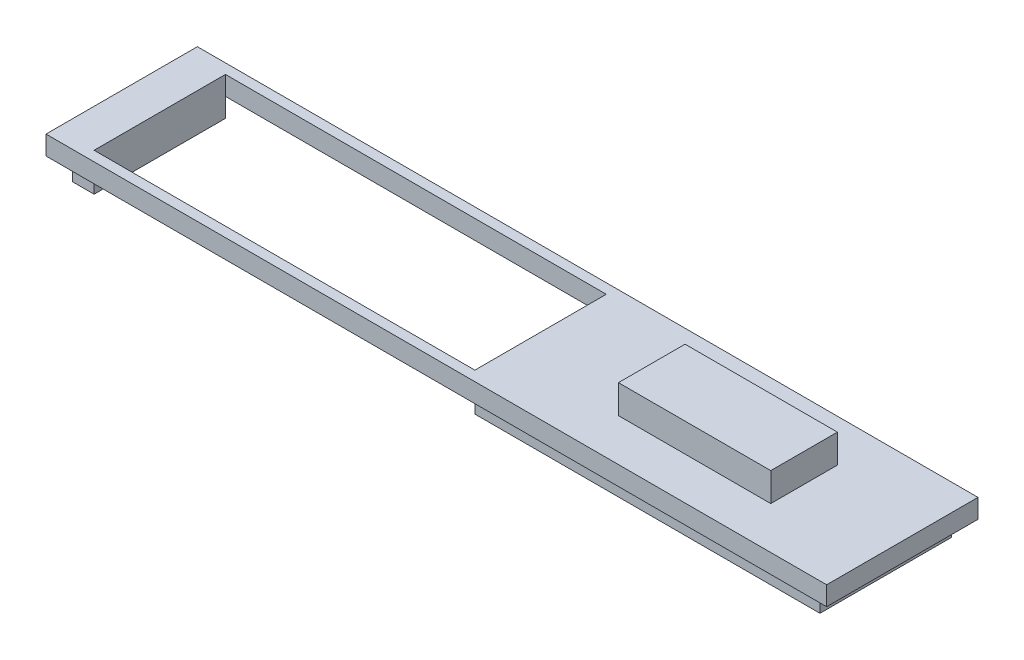
SolidWorks part; units mm, degrees
ref_plane "Front Plane" through (0, 0, 0) normal (0, 0, 1) x (1, 0, 0)
ref_plane "Top Plane" through (0, 0, 0) normal (0, 1, 0) x (1, 0, 0)
ref_plane "Right Plane" through (0, 0, 0) normal (1, 0, 0) x (0, 0, -1)
sketch "Sketch1" plane through (0, 0, 0) normal (0, 1, 0) x (1, 0, 0)
  line L1 (49.8475, -8.763) -> (-49.8475, -8.763)
  line L2 (49.8475, -8.763) -> (49.8475, 8.763)
  line L3 (49.8475, 8.763) -> (-49.8475, 8.763)
  line L4 (-49.8475, -8.763) -> (-49.8475, 8.763)
  line L5 (49.8475, -8.763) -> (-49.8475, 8.763) construction
  line L6 (49.8475, 8.763) -> (-49.8475, -8.763) construction
  point P0 (0, 0)
  dimension "D1" = 99.695
  dimension "D2" = 17.526
extrude "Boss-Extrude1" add sketch "Sketch1" along normal blind 2.54
sketch "Sketch2" plane through (0, 2.54, 0) normal (0, 1, 0) x (1, 0, 0)
  line L1 (52.07, -10.0965) -> (-52.07, -10.0965)
  line L2 (52.07, -10.0965) -> (52.07, 10.0965)
  line L3 (52.07, 10.0965) -> (-52.07, 10.0965)
  line L4 (-52.07, -10.0965) -> (-52.07, 10.0965)
  line L5 (52.07, -10.0965) -> (-52.07, 10.0965) construction
  line L6 (52.07, 10.0965) -> (-52.07, -10.0965) construction
  point P0 (0, 0)
  dimension "D1" = 104.14
  dimension "D2" = 20.193
extrude "Boss-Extrude2" add sketch "Sketch2" along normal blind 2.54
sketch "Sketch4" plane through (0, 5.08, 0) normal (0, 1, 0) x (1, 0, 0)
  line L0 (52.07, 0) -> (-52.07, 0) construction
  line L1 (-52.07, 10.0965) -> (-52.07, -10.0965) construction
  line L4 (18.6436, -4.445) -> (38.9636, -4.445)
  line L5 (18.6436, -4.445) -> (18.6436, 4.445)
  line L6 (18.6436, 4.445) -> (38.9636, 4.445)
  line L7 (38.9636, -4.445) -> (38.9636, 4.445)
  line L8 (18.6436, -4.445) -> (38.9636, 4.445) construction
  line L9 (18.6436, 4.445) -> (38.9636, -4.445) construction
  point P0 (0, 0)
  point P1 (28.8036, 0)
  point P7 (0, 0)
  dimension "D1" = 8.89
  dimension "D2" = 20.32
extrude "Boss-Extrude3" add sketch "Sketch4" along normal blind 3.81
sketch "Sketch5" plane through (0, 5.08, 0) normal (0, 1, 0) x (1, 0, 0)
  line L0 (52.07, 0) -> (-52.07, 0) construction
  line L1 (-52.07, 10.0965) -> (-52.07, -10.0965) construction
  line L3 (3.81, -8.763) -> (-46.99, -8.763)
  line L4 (3.81, -8.763) -> (3.81, 8.763)
  line L5 (3.81, 8.763) -> (-46.99, 8.763)
  line L6 (-46.99, -8.763) -> (-46.99, 8.763)
  line L7 (3.81, -8.763) -> (-46.99, 8.763) construction
  line L8 (3.81, 8.763) -> (-46.99, -8.763) construction
  point P0 (-21.59, 0)
  point P6 (0, 0)
  dimension "D1" = 5.08
  dimension "D2" = 50.8
  dimension "D3" = 17.526
extrude "Cut-Extrude1" cut sketch "Sketch5" against normal through all
